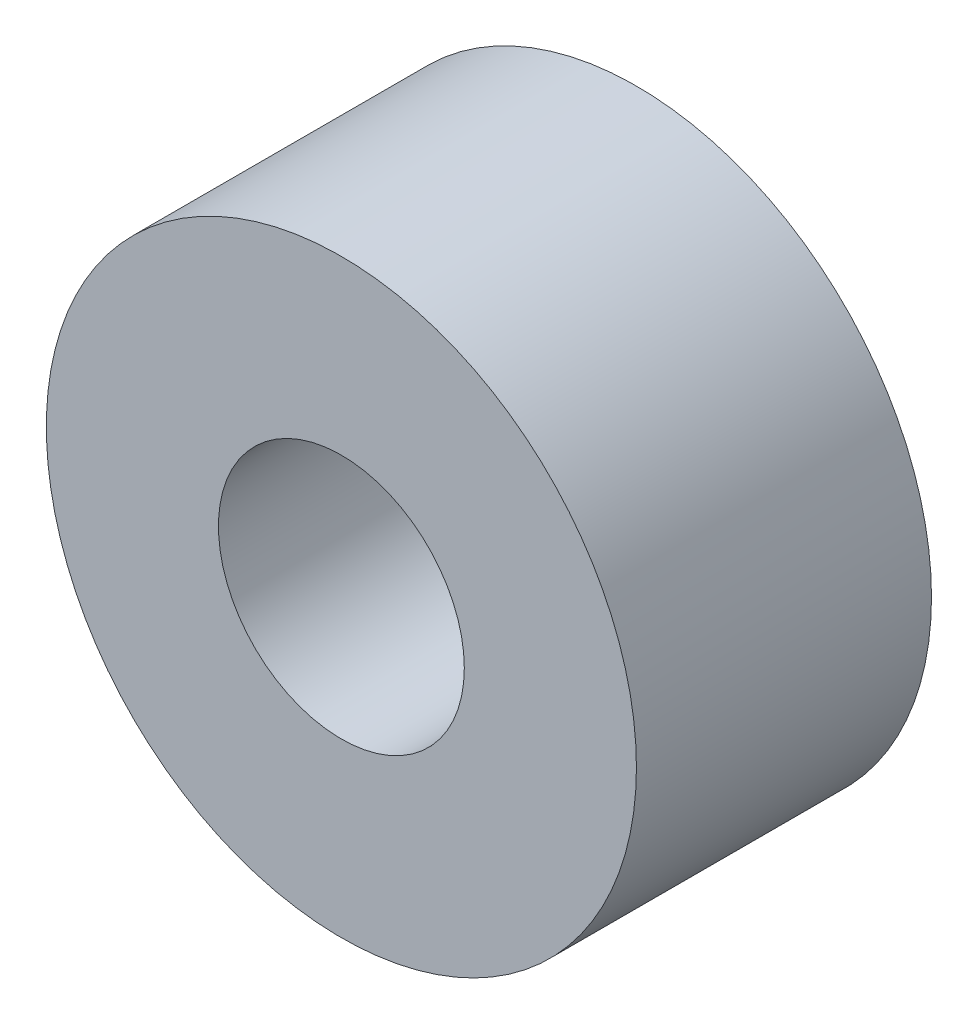
SolidWorks part; units mm, degrees
ref_plane "Ön Düzlem" through (0, 0, 0) normal (0, 0, 1) x (1, 0, 0)
ref_plane "Üst Düzlem" through (0, 0, 0) normal (0, 1, 0) x (1, 0, 0)
ref_plane "Sağ Düzlem" through (0, 0, 0) normal (1, 0, 0) x (0, 0, -1)
sketch "Sketch1" plane through (0, 0, 0) normal (0, 0, 1) x (1, 0, 0)
  circle A0 centre (0, 0) radius 7.5
  circle A1 centre (0, 0) radius 18
extrude "Boss-Extrude1" add sketch "Sketch1" along normal blind 18
